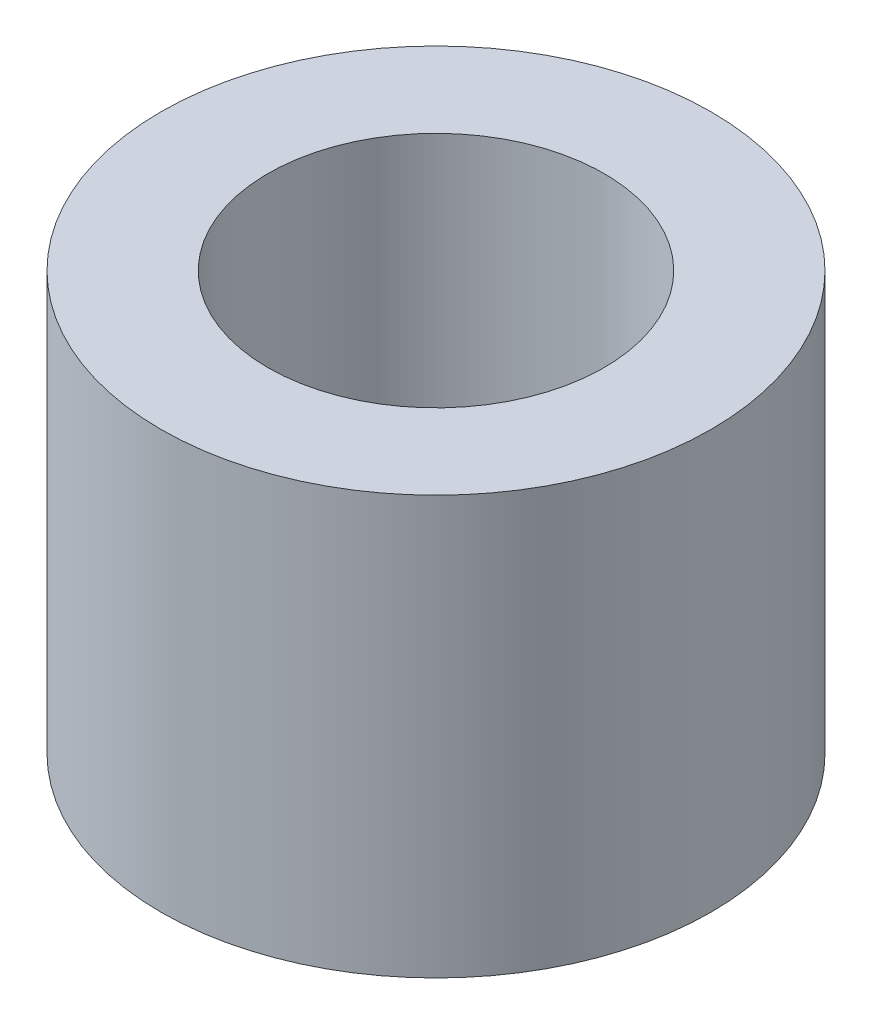
SolidWorks part; units mm, degrees
material "6061-T6 (SS)"
ref_plane "Front Plane" through (0, 0, 0) normal (0, 0, 1) x (1, 0, 0)
ref_plane "Top Plane" through (0, 0, 0) normal (0, 1, 0) x (1, 0, 0)
ref_plane "Right Plane" through (0, 0, 0) normal (1, 0, 0) x (0, 0, -1)
sketch "Sketch1" plane through (0, 0, 0) normal (0, 1, 0) x (1, 0, 0)
  circle A0 centre (0, 0) radius 7.9375
  circle A1 centre (0, 0) radius 4.8514
  dimension "D1" = 9.7028
  dimension "D2" = 15.875
extrude "Boss-Extrude1" add sketch "Sketch1" along normal blind 2.54 and the other way blind 9.525
